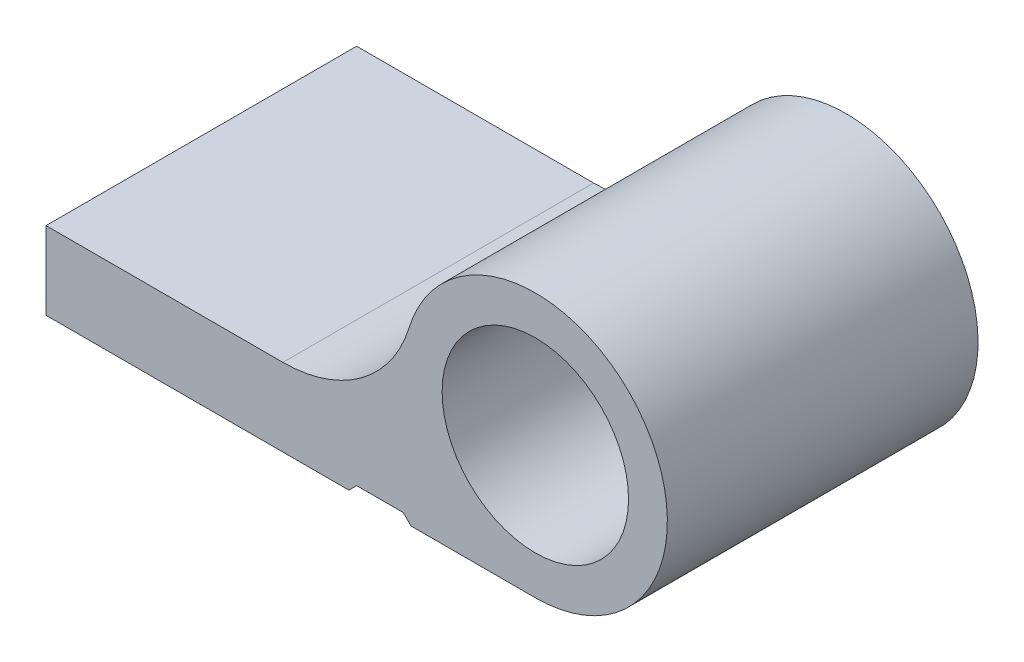
SolidWorks part; units mm, degrees
ref_plane "前视基准面" through (0, 0, 0) normal (0, 0, 1) x (1, 0, 0)
ref_plane "上视基准面" through (0, 0, 0) normal (0, 1, 0) x (1, 0, 0)
ref_plane "右视基准面" through (0, 0, 0) normal (1, 0, 0) x (0, 0, -1)
other "Configuration Table"
sketch "草图1" plane through (0, 0, 0) normal (0, 1, 0) x (1, 0, 0)
  line L1 (0, 0) -> (20, 0)
  line L2 (0, 0) -> (0, -20)
  line L3 (0, -20) -> (20, -20)
  line L4 (20, 0) -> (20, -20)
  line L5 (20, 0) -> (23, 0)
  line L6 (20, 0) -> (20, -20)
  line L7 (20, -20) -> (23, -20)
  line L8 (23, 0) -> (23, -20)
  line L9 (23, 0) -> (43, 0)
  line L10 (23, 0) -> (23, -20)
  line L11 (23, -20) -> (43, -20)
  line L12 (43, 0) -> (43, -20)
sketch "草图2" plane through (0, 0, 0) normal (0, 0, 1) x (1, 0, 0)
  line L0 (0, 0) -> (0, 5)
  line L1 (0, 0) -> (20, 0)
  line L2 (0, 0) -> (20, 0) construction
  line L3 (20, 0) -> (23, 0) construction
  line L16 (20, 0) -> (23, 0)
  line L21 (23, 0) -> (43, 0) construction
  line L23 (23, 0) -> (31.5, 0)
  line L26 (23, 8.5) -> (23, 5)
  line L27 (23, 5) -> (0, 5)
  circle A5 centre (31.5, 8.5) radius 6
  arc A6 (23, 8.5) -> (31.5, 0) centre (31.5, 8.5) cw
extrude "凸台-拉伸1" add sketch "草图2" along normal blind 20 contours A6 L26 L27 L0 L1 L16 L23 A5
fillet "圆角1" radius 8.5 1 edges at (23, 5, 10)
sketch "草图3" plane through (0, 0, 20) normal (0, 0, 1) x (1, 0, 0)
  line L0 (0, 0) -> (20, 0)
  line L1 (20, 0) -> (23, 0) construction
  line L2 (0, 0) -> (20, 0) construction
  line L3 (20, 0) -> (20, 0.5)
  line L4 (20, 0.5) -> (23, 0.5)
  line L5 (23, 0.5) -> (23, 0)
  line L6 (23, 0) -> (43, 0) construction
  line L7 (20, 0) -> (23, 0)
  line M6 (0, 0) -> (31.5, 0)
extrude "切除-拉伸1" cut sketch "草图3" against normal blind 100 contours L5 L4 L3 M6
sketch "草图4" plane through (0, 0, 20) normal (0, 0, 1) x (1, 0, 0)
  line L0 (23, 0) -> (23.5, 0)
  line L1 (23, 0) -> (43, 0) construction
  line L2 (23, 0) -> (23, 0.5)
  line L3 (23, 0.5) -> (23.5, 0)
  line L4 (20, 0) -> (19.5, 0)
  line L5 (0, 0) -> (20, 0) construction
  line L6 (19.5, 0) -> (20, 0.5)
  line L7 (20, 0.5) -> (20, 0)
extrude "切除-拉伸2" cut sketch "草图4" against normal blind 100
